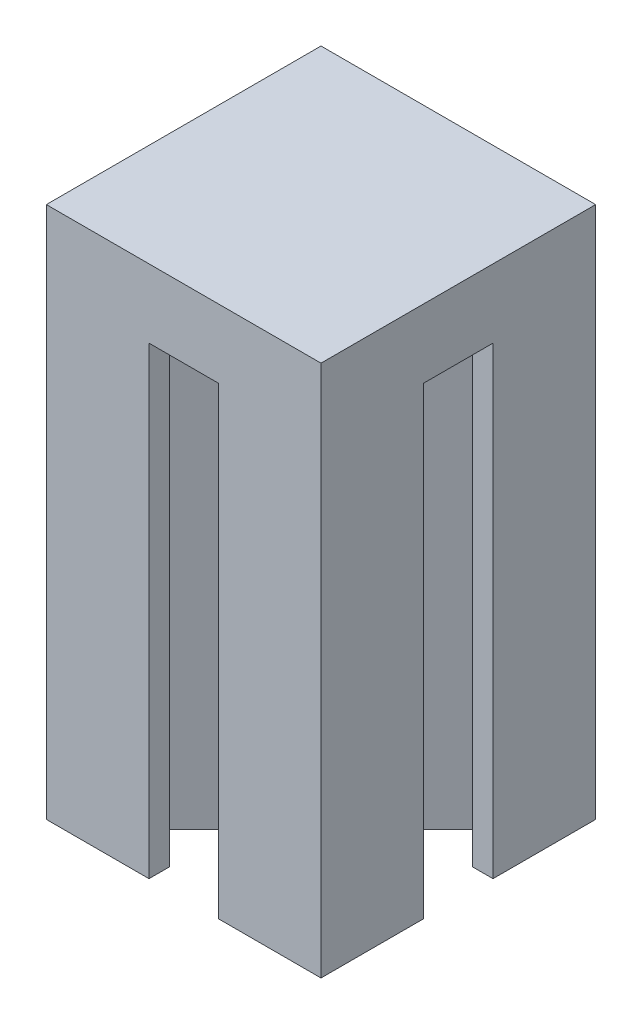
SolidWorks part; units mm, degrees
ref_plane "Front Plane" through (0, 0, 0) normal (0, 0, 1) x (1, 0, 0)
ref_plane "Top Plane" through (0, 0, 0) normal (0, 1, 0) x (1, 0, 0)
ref_plane "Right Plane" through (0, 0, 0) normal (1, 0, 0) x (0, 0, -1)
ref_plane "Plane1" through (0, 75.9946, 0) normal (0, 1, 0) x (1, 0, 0)
sketch "Sketch1" plane through (0, 75.9946, 0) normal (0, 1, 0) x (1, 0, 0)
  line L0 (-75.1775, -15.0399) -> (-60.2275, -15.0399)
  line L1 (-60.2275, -15.0399) -> (-60.2275, -12.0399)
  line L2 (-60.2275, -12.0399) -> (-65.1775, -12.0399)
  line L3 (-65.1775, -12.0399) -> (-65.1775, -12.5399)
  line L4 (-65.1775, -12.5399) -> (-67.7633, -12.5399)
  line L5 (-68.4704, -10.8328) -> (-60.6775, -3.0399)
  line L6 (-60.6775, -3.0399) -> (-49.6775, -3.0399)
  line L7 (-49.6775, -3.0399) -> (-41.8846, -10.8328)
  line L8 (-42.5917, -12.5399) -> (-45.1775, -12.5399)
  line L9 (-45.1775, -12.5399) -> (-45.1775, -12.0399)
  line L10 (-45.1775, -12.0399) -> (-50.1275, -12.0399)
  line L11 (-50.1275, -12.0399) -> (-50.1275, -15.0399)
  line L12 (-50.1275, -15.0399) -> (-35.1775, -15.0399)
  line L13 (-35.1775, -15.0399) -> (-35.1775, -0.0899)
  line L14 (-35.1775, -0.0899) -> (-38.1775, -0.0899)
  line L15 (-38.1775, -0.0899) -> (-38.1775, -5.0399)
  line L16 (-38.1775, -5.0399) -> (-37.6775, -5.0399)
  line L17 (-37.6775, -5.0399) -> (-37.6775, -7.6257)
  line L18 (-39.3846, -8.3328) -> (-47.1775, -0.5399)
  line L19 (-47.1775, -0.5399) -> (-47.1775, 10.4601)
  line L20 (-47.1775, 10.4601) -> (-39.3846, 18.253)
  line L21 (-37.6775, 17.5459) -> (-37.6775, 14.9601)
  line L22 (-37.6775, 14.9601) -> (-38.1775, 14.9601)
  line L23 (-38.1775, 14.9601) -> (-38.1775, 10.0101)
  line L24 (-38.1775, 10.0101) -> (-35.1775, 10.0101)
  line L25 (-35.1775, 10.0101) -> (-35.1775, 24.9601)
  line L26 (-35.1775, 24.9601) -> (-50.1275, 24.9601)
  line L27 (-50.1275, 24.9601) -> (-50.1275, 21.9601)
  line L28 (-50.1275, 21.9601) -> (-45.1775, 21.9601)
  line L29 (-45.1775, 21.9601) -> (-45.1775, 22.4601)
  line L30 (-45.1775, 22.4601) -> (-42.5917, 22.4601)
  line L31 (-41.8846, 20.753) -> (-49.6775, 12.9601)
  line L32 (-49.6775, 12.9601) -> (-60.6775, 12.9601)
  line L33 (-60.6775, 12.9601) -> (-68.4704, 20.753)
  line L34 (-67.7633, 22.4601) -> (-65.1775, 22.4601)
  line L35 (-65.1775, 22.4601) -> (-65.1775, 21.9601)
  line L36 (-65.1775, 21.9601) -> (-60.2275, 21.9601)
  line L37 (-60.2275, 21.9601) -> (-60.2275, 24.9601)
  line L38 (-60.2275, 24.9601) -> (-75.1775, 24.9601)
  line L39 (-75.1775, 24.9601) -> (-75.1775, 10.0101)
  line L40 (-75.1775, 10.0101) -> (-72.1775, 10.0101)
  line L41 (-72.1775, 10.0101) -> (-72.1775, 14.9601)
  line L42 (-72.1775, 14.9601) -> (-72.6775, 14.9601)
  line L43 (-72.6775, 14.9601) -> (-72.6775, 17.5459)
  line L44 (-70.9704, 18.253) -> (-63.1775, 10.4601)
  line L45 (-63.1775, 10.4601) -> (-63.1775, -0.5399)
  line L46 (-63.1775, -0.5399) -> (-70.9704, -8.3328)
  line L47 (-72.6775, -7.6257) -> (-72.6775, -5.0399)
  line L48 (-72.6775, -5.0399) -> (-72.1775, -5.0399)
  line L49 (-72.1775, -5.0399) -> (-72.1775, -0.0899)
  line L50 (-72.1775, -0.0899) -> (-75.1775, -0.0899)
  line L51 (-75.1775, -0.0899) -> (-75.1775, -15.0399)
  arc A0 (-67.7633, -12.5399) -> (-68.4704, -10.8328) centre (-67.7633, -11.5399) cw
  arc A1 (-41.8846, -10.8328) -> (-42.5917, -12.5399) centre (-42.5917, -11.5399) cw
  arc A2 (-37.6775, -7.6257) -> (-39.3846, -8.3328) centre (-38.6775, -7.6257) cw
  arc A3 (-39.3846, 18.253) -> (-37.6775, 17.5459) centre (-38.6775, 17.5459) cw
  arc A4 (-42.5917, 22.4601) -> (-41.8846, 20.753) centre (-42.5917, 21.4601) cw
  arc A5 (-68.4704, 20.753) -> (-67.7633, 22.4601) centre (-67.7633, 21.4601) cw
  arc A6 (-72.6775, 17.5459) -> (-70.9704, 18.253) centre (-71.6775, 17.5459) cw
  arc A7 (-70.9704, -8.3328) -> (-72.6775, -7.6257) centre (-71.6775, -7.6257) cw
extrude "Boss-Extrude1" add sketch "Sketch1" against normal blind 67.55
sketch "Sketch2" plane through (0, 75.9946, 0) normal (0, 1, 0) x (1, 0, 0)
  line L1 (-75.1775, 24.9601) -> (-35.1775, 24.9601)
  line L2 (-75.1775, 24.9601) -> (-75.1775, -15.0399)
  line L3 (-75.1775, -15.0399) -> (-35.1775, -15.0399)
  line L4 (-35.1775, 24.9601) -> (-35.1775, -15.0399)
extrude "Boss-Extrude2" add sketch "Sketch2" along normal blind 10
